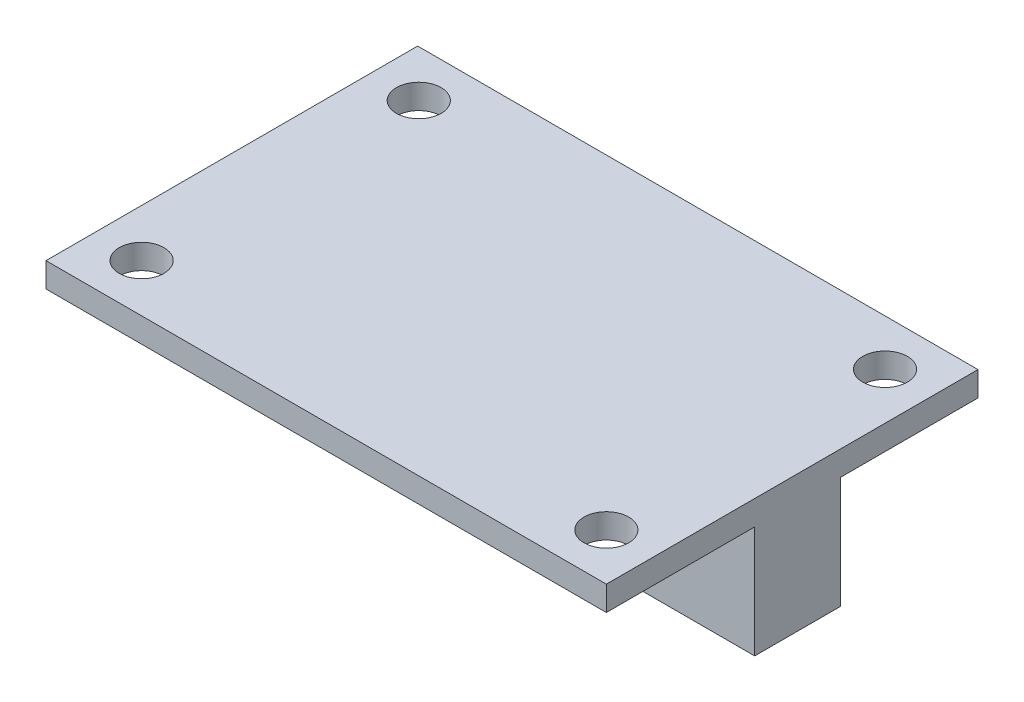
SolidWorks part; units mm, degrees
ref_plane "Front Plane" through (0, 0, 0) normal (0, 0, 1) x (1, 0, 0)
ref_plane "Top Plane" through (0, 0, 0) normal (0, 1, 0) x (1, 0, 0)
ref_plane "Right Plane" through (0, 0, 0) normal (1, 0, 0) x (0, 0, -1)
sketch "Sketch1" plane through (0, 0, 0) normal (0, 1, 0) x (1, 0, 0)
  line L1 (-19.1005, 12.6687) -> (19.1005, 12.6687)
  line L2 (-19.1005, 12.6687) -> (-19.1005, -12.6687)
  line L3 (-19.1005, -12.6687) -> (19.1005, -12.6687)
  line L4 (19.1005, 12.6687) -> (19.1005, -12.6687)
  line L5 (-19.1005, 12.6687) -> (19.1005, -12.6687) construction
  line L6 (-19.1005, -12.6687) -> (19.1005, 12.6687) construction
  point P0 (0, 0)
extrude "Boss-Extrude1" add sketch "Sketch1" along normal blind 1.6764
sketch "Sketch2" plane through (0, 1.6764, 0) normal (0, 1, 0) x (1, 0, 0)
  line L0 (0, 12.6687) -> (0, -12.6687) construction
  line L1 (19.1005, 12.6687) -> (-19.1005, 12.6687) construction
  line L2 (-19.1005, -12.6687) -> (19.1005, -12.6687) construction
  line L3 (-19.1005, 12.6687) -> (-19.1005, -12.6687) construction
  line L4 (19.1005, -12.6687) -> (19.1005, 12.6687) construction
  line L6 (-19.1005, 12.6687) -> (19.1005, 12.6687)
  line L7 (-19.1005, 12.6687) -> (-19.1005, -12.6687)
  line L8 (-19.1005, -12.6687) -> (19.1005, -12.6687)
  line L9 (19.1005, 12.6687) -> (19.1005, -12.6687)
  line L10 (-19.1005, 12.6687) -> (19.1005, -12.6687) construction
  line L11 (-19.1005, -12.6687) -> (19.1005, 12.6687) construction
  circle A0 centre (-15.8493, -9.4048) radius 1.524
  circle A1 centre (-15.8493, 9.4937) radius 1.524
  circle A2 centre (15.9128, 9.5191) radius 1.524
  circle A3 centre (15.9001, -9.4683) radius 1.524
  point P18 (0, 0)
  dimension "D1" = 3.2639
  dimension "D2" = 3.2512
  dimension "D3" = 3.2512
  dimension "D5" = 3.1877
  dimension "D6" = 3.2004
  dimension "D4" = 3.175
  dimension "D7" = 3.2004
extrude "Cut-Extrude1" cut sketch "Sketch2" against normal blind 1.6764 contours A1 | A0 | A3 | A2
sketch "Sketch5" plane through (0, 0, 0) normal (0, -1, 0) x (1, 0, 0)
  line L0 (19.1005, 12.6687) -> (19.1005, -12.6687) construction
  line L1 (19.1005, 2.5559) -> (11.3391, 2.5559)
  line L2 (19.1005, 2.5559) -> (19.1005, -3.2861)
  line L3 (19.1005, -3.2861) -> (11.3391, -3.2861)
  line L4 (11.3391, 2.5559) -> (11.3391, -3.2861)
extrude "Boss-Extrude2" add sketch "Sketch5" along normal blind 7.62
